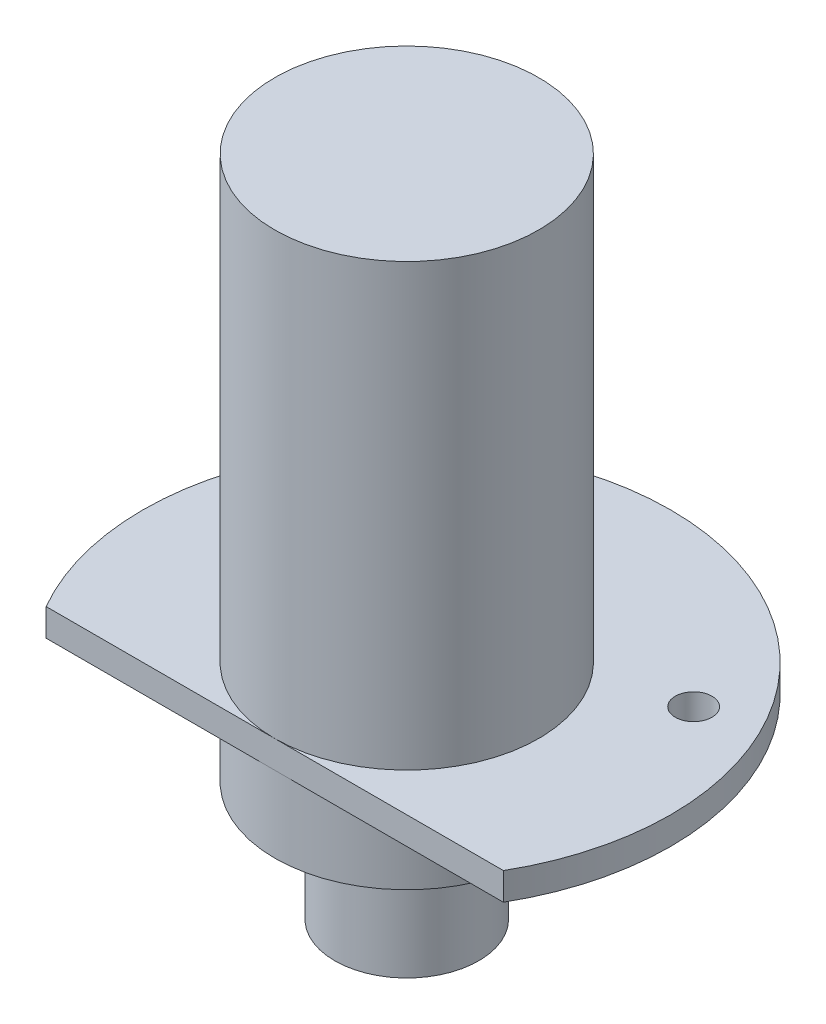
SolidWorks part; units mm, degrees
material "6061-T6 (SS)"
ref_plane "Front Plane" through (0, 0, 0) normal (0, 0, 1) x (1, 0, 0)
ref_plane "Top Plane" through (0, 0, 0) normal (0, 1, 0) x (1, 0, 0)
ref_plane "Right Plane" through (0, 0, 0) normal (1, 0, 0) x (0, 0, -1)
sketch "Sketch1" plane through (0, 0, 0) normal (1, 0, 0) x (0, 0, -1)
  line L0 (0, 55.245) -> (0, 0) construction
  line L1 (11, 18.542) -> (22, 18.542)
  line L2 (11, 18.542) -> (11, 55.245)
  line L3 (11, 55.245) -> (0, 55.245)
  line L4 (0, 55.245) -> (0, 0)
  line L6 (22, 18.542) -> (22, 16.256)
  line L7 (22, 16.256) -> (11, 16.256)
  line L8 (11, 16.256) -> (11, 9.906)
  line L9 (11, 9.906) -> (6, 9.906)
  line L10 (6, 9.906) -> (6, 0)
  line L11 (6, 0) -> (0, 0)
  dimension "D2" = 22
  dimension "D1" = 44
  dimension "D6" = 12
  dimension "D7" = 55.245
  dimension "D3" = 36.703
  dimension "D4" = 2.286
  dimension "D5" = 6.35
revolve "Revolve1" add sketch "Sketch1" angle 360 about L0
sketch "Sketch2" plane through (0, 16.256, 0) normal (0, -1, 0) x (1, 0, 0)
  circle A0 centre (0, 0) radius 17.5 construction
  circle A1 centre (0, 17.5) radius 1.527
  circle A2 centre (15.1554, -8.75) radius 1.527
  circle A3 centre (-15.1554, -8.75) radius 1.527
  point P11 (0, 0)
  dimension "D1" = 35
  dimension "D2" = 3.054
  dimension "D3" = 3
extrude "Cut-Extrude1" cut sketch "Sketch2" against normal through all
sketch "Sketch4" plane through (0, 18.542, 0) normal (0, 1, 0) x (1, 0, 0)
  line L0 (-19.0526, -11) -> (19.0526, -11)
  circle A0 centre (0, 0) radius 22 construction
  circle A1 centre (0, 0) radius 11 construction
  arc A2 (-19.0526, -11) -> (19.0526, -11) centre (0, 0) ccw
  point P4 (18.5954, -11.7564)
extrude "Cut-Extrude2" cut sketch "Sketch4" against normal through all both and the other way through all
equation "\"D2@Sketch1\"=22mm"
equation "\"D1@Sketch1\"=44mm"
equation "\"D6@Sketch1\"=12mm"
equation "\"D1@Sketch2\"=35mm"
equation "\"D2@Sketch2\"=3.054mm"
